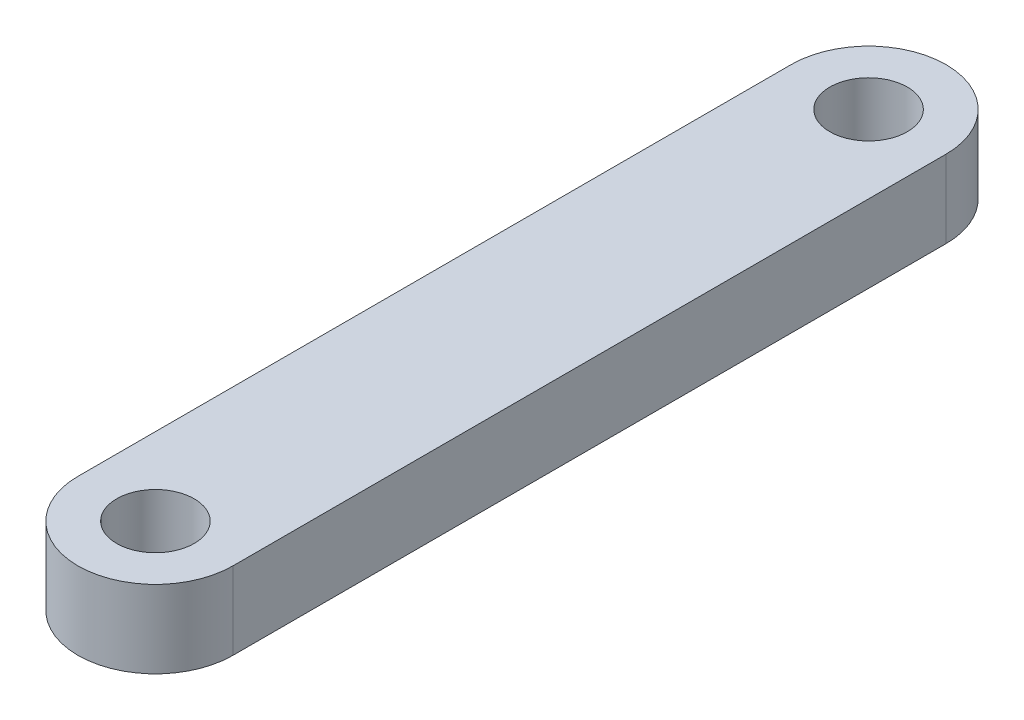
SolidWorks part; units mm, degrees
ref_plane "Front Plane" through (0, 0, 0) normal (0, 0, 1) x (1, 0, 0)
ref_plane "Top Plane" through (0, 0, 0) normal (0, 1, 0) x (1, 0, 0)
ref_plane "Right Plane" through (0, 0, 0) normal (1, 0, 0) x (0, 0, -1)
sketch "Sketch1" plane through (0, 0, 0) normal (0, 1, 0) x (1, 0, 0)
  line L0 (0, 0) -> (0, 58.42) construction
  line L1 (-6.35, 0) -> (-6.35, 58.42)
  line L2 (6.35, 0) -> (6.35, 58.42)
  arc A0 (-6.35, 0) -> (6.35, 0) centre (0, 0) ccw
  arc A1 (6.35, 58.42) -> (-6.35, 58.42) centre (0, 58.42) ccw
  circle A2 centre (0, 58.42) radius 3.175
  circle A3 centre (0, 0) radius 3.175
  point P3 (0, 29.21)
  dimension "D2" = 6.35
  dimension "D3" = 6.35
  dimension "D1" = 58.42
extrude "Boss-Extrude1" add sketch "Sketch1" along normal mid plane 6.35
